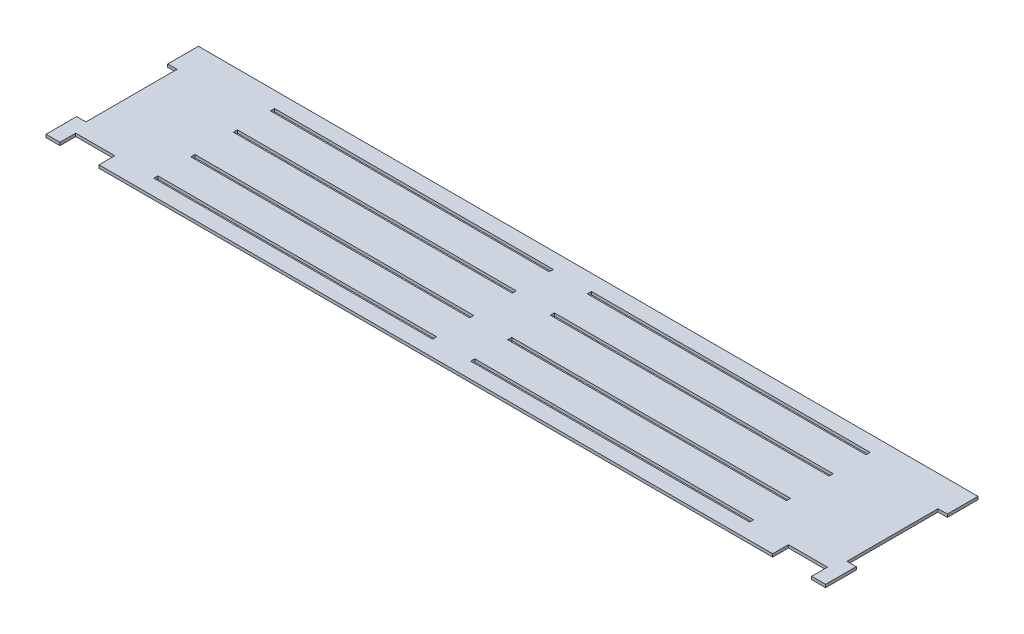
SolidWorks part; units mm, degrees
ref_plane "Plan de face" through (0, 0, 0) normal (0, 0, 1) x (1, 0, 0)
ref_plane "Plan de dessus" through (0, 0, 0) normal (0, 1, 0) x (1, 0, 0)
ref_plane "Plan de droite" through (0, 0, 0) normal (1, 0, 0) x (0, 0, -1)
sketch "Esquisse1" plane through (0, 0, 0) normal (0, 1, 0) x (1, 0, 0)
  line L1 (-209.75, -41) -> (209.75, -41)
  line L2 (-209.75, -41) -> (-209.75, 41)
  line L3 (-209.75, 41) -> (209.75, 41)
  line L4 (209.75, -41) -> (209.75, 41)
  line L5 (-209.75, -41) -> (209.75, 41) construction
  line L6 (-209.75, 41) -> (209.75, -41) construction
  point P0 (0, 0)
  dimension "D1" = 419.5
  dimension "D2" = 82
extrude "Boss.-Extru.1" add sketch "Esquisse1" along normal blind 1.5875 contours L3 L4 L1 L2
sketch "Esquisse2" plane through (0, 1.5875, 0) normal (0, 1, 0) x (1, 0, 0)
  line L0 (-209.75, -41) -> (-209.75, 41) construction
  line L1 (-209.75, 24.5) -> (-204.75, 24.5)
  line L2 (-209.75, 24.5) -> (-209.75, -24.5)
  line L3 (-209.75, -24.5) -> (-204.75, -24.5)
  line L4 (-204.75, 24.5) -> (-204.75, -24.5)
  point P6 (-204.75, 0)
  dimension "D1" = 5
  dimension "D2" = 49
extrude "Enlèv. mat.-Extru.1" cut sketch "Esquisse2" against normal through all
mirror "Symétrie1" about plane through (0, 0, 0) normal (1, 0, 0) of "Enlèv. mat.-Extru.1"
sketch "Esquisse3" plane through (0, 1.5875, 0) normal (0, 1, 0) x (1, 0, 0)
  line L0 (10.25, 32.4815) -> (160.25, 32.4815)
  line L8 (160.25, 32.4815) -> (160.25, 30.2815)
  line L10 (10.25, 30.2815) -> (10.25, 32.4815)
  line L13 (10.25, 31.3815) -> (0, 31.3815) construction
  line L15 (10.25, 30.2815) -> (160.25, 30.2815)
  point P0 (0, 31.3815)
  point P1 (85.25, 30.2815)
  dimension "D1" = 2.2
  dimension "D2" = 31.3815
  dimension "D3" = 85.25
  dimension "D4" = 2.2
  dimension "D6" = 150
extrude "Enlèv. mat.-Extru.2" cut sketch "Esquisse3" against normal through all
pattern_linear "Répétition linéaire1" count 2 spacing 19.921 along (0, 0, 1) of "Enlèv. mat.-Extru.2"
mirror "Symétrie5" about plane through (0, 0, 0) normal (1, 0, 0) of "Répétition linéaire1", "Enlèv. mat.-Extru.2"
sketch "Esquisse5" plane through (0, 0, 0) normal (0, -1, 0) x (1, 0, 0)
  line L0 (-209.75, 41) -> (209.75, 41) construction
  line L1 (181.25, 41) -> (202.25, 41)
  line L2 (181.25, 41) -> (181.25, 32.5)
  line L3 (181.25, 32.5) -> (202.25, 32.5)
  line L4 (202.25, 41) -> (202.25, 32.5)
  line L5 (209.75, 41) -> (209.75, 24.5) construction
  line L6 (0, 0) -> (0, 41) construction
  line L7 (-202.25, 41) -> (-202.25, 32.5)
  line L8 (-181.25, 32.5) -> (-202.25, 32.5)
  line L9 (-181.25, 41) -> (-181.25, 32.5)
  line L10 (-181.25, 41) -> (-202.25, 41)
  dimension "D1" = 7.5
  dimension "D2" = 21
  dimension "D3" = 8.5
extrude "Enlèv. mat.-Extru.3" cut sketch "Esquisse5" against normal up to next
mirror "Symétrie6" about plane through (0, 0, 0) normal (0, 0, 1) of "Symétrie5", "Enlèv. mat.-Extru.2", "Répétition linéaire1"
